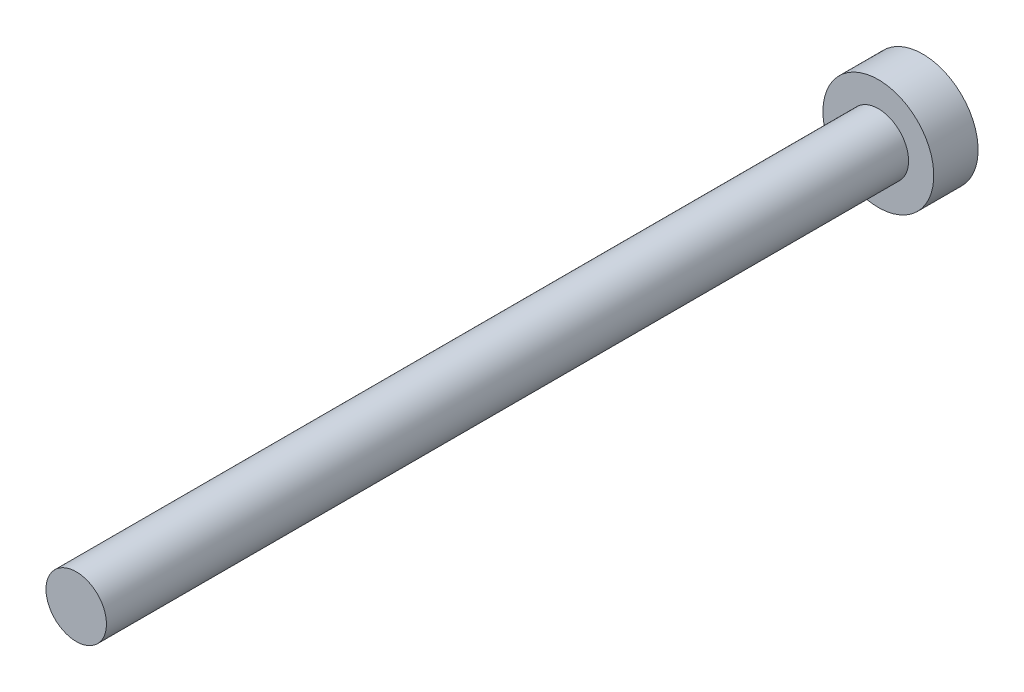
SolidWorks part; units mm, degrees
ref_plane "Front Plane" through (0, 0, 0) normal (0, 0, 1) x (1, 0, 0)
ref_plane "Top Plane" through (0, 0, 0) normal (0, 1, 0) x (1, 0, 0)
ref_plane "Right Plane" through (0, 0, 0) normal (1, 0, 0) x (0, 0, -1)
sketch "Sketch1" plane through (0, 0, 0) normal (0, 0, 1) x (1, 0, 0)
  circle A0 centre (0, 0) radius 1.5
  dimension "D1" = 3
extrude "Boss-Extrude1" add sketch "Sketch1" along normal blind 42
sketch "Sketch2" plane through (0, 0, 0) normal (0, 0, -1) x (-1, 0, 0)
  circle A0 centre (0, 0) radius 2.75
  dimension "D1" = 5.5
extrude "Boss-Extrude2" add sketch "Sketch2" against normal blind 2.2
scale "Escala1" scale about origin uniform scaling yes scale factor 1.5
scale "Escala2" scale about origin uniform scaling yes scale factor 1.5
